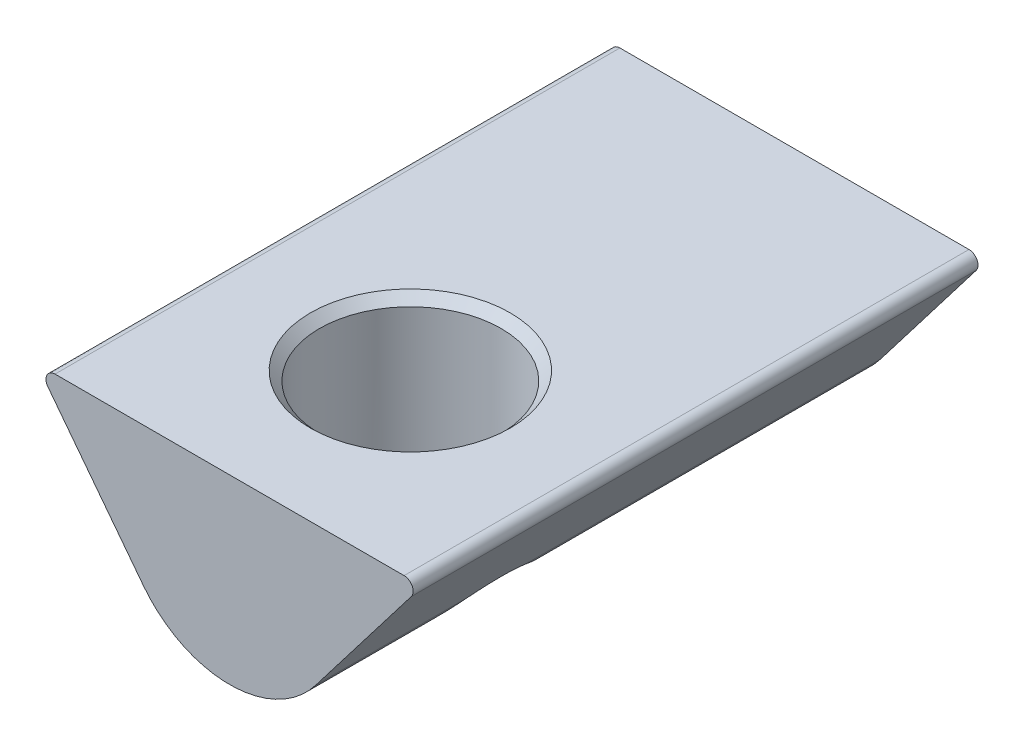
SolidWorks part; units mm, degrees
ref_plane "Front Plane" through (0, 0, 0) normal (0, 0, 1) x (1, 0, 0)
ref_plane "Top Plane" through (0, 0, 0) normal (0, 1, 0) x (1, 0, 0)
ref_plane "Right Plane" through (0, 0, 0) normal (1, 0, 0) x (0, 0, -1)
sketch "Model" plane through (0, 0, 0) normal (0, 0, 1) x (1, 0, 0)
  line L0 (15.7736, 23.3058) -> (25.5841, 23.3058)
  line L1 (15.5195, 23.0517) -> (15.5195, 23.6809) construction
  line L2 (25.8382, 23.0517) -> (25.8382, 23.6419) construction
  line L3 (25.8382, 23.3058) -> (15.5195, 23.3058) construction
  line L55 (15.572, 22.897) -> (18.2592, 19.3949)
  line L57 (23.0985, 19.3949) -> (25.7857, 22.897)
  arc A2 (15.7736, 23.3058) -> (15.572, 22.897) centre (15.7736, 23.0517) ccw
  arc A3 (25.7857, 22.897) -> (25.5841, 23.3058) centre (25.5841, 23.0517) ccw
  arc A4 (18.2592, 19.3949) -> (23.0985, 19.3949) centre (20.6788, 21.2516) ccw
  dimension "D1" = 10.3187
  dimension "D2" = 0.2542
  dimension "D3" = 3.0499
  dimension "D4" = 15.5195
  dimension "D5" = 15.572
  dimension "D6" = 19.3949
extrude "Boss-Extrude1" add sketch "Model" along normal blind 15.875
hole_wizard "Tap Drill for 1/4-20 Tap1" positions "Sketch2" profile "Sketch4" hole size "1/4-20" standard "ANSI Inch" end condition through all
sketch "Sketch2" plane through (0, 23.3058, 0) normal (0, 1, 0) x (1, 0, 0)
  line L0 (15.7736, -10.795) -> (25.5841, -10.795) construction
  line L1 (15.7736, -15.875) -> (15.7736, 0) construction
  line L2 (25.5841, -15.875) -> (25.5841, 0) construction
  line L3 (25.5841, -15.875) -> (15.7736, -15.875) construction
  point P10 (20.6788, -10.795)
  dimension "D1" = 5.08
sketch "Sketch4" plane through (20.6788, 23.3058, 10.795) normal (1, 0, 0) x (0, 0, 1)
  line L0 (0, 0) -> (0, 5.1042)
  line L1 (0, 5.1042) -> (2.5527, 5.1042)
  line L2 (2.5527, 5.1042) -> (2.5527, 0)
  line L5 (2.5527, 0) -> (0, 0)
  line L11 (0, -6.35) -> (0, 107.95) construction
  dimension "Thru Hole Dia." = 5.1054
  dimension "Thru Hole Depth" = 5.1042
chamfer "Chamfer1" distance 0.254 angle 45 1 edges at (20.6788, 23.3058, 13.3477)
